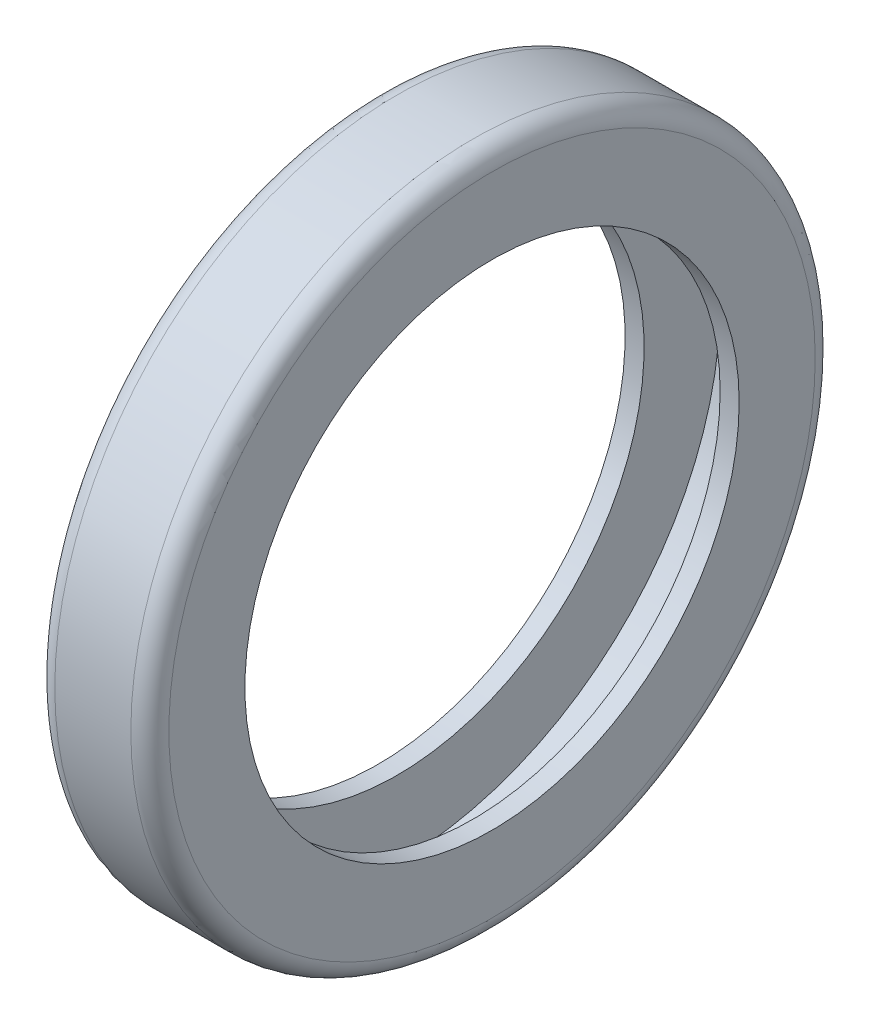
SolidWorks part; units mm, degrees
ref_plane "Plan de face" through (0, 0, 0) normal (0, 0, 1) x (1, 0, 0)
ref_plane "Plan de dessus" through (0, 0, 0) normal (0, 1, 0) x (1, 0, 0)
ref_plane "Plan de droite" through (0, 0, 0) normal (1, 0, 0) x (0, 0, -1)
sketch "Esquisse1" plane through (0, 0, 0) normal (1, 0, 0) x (0, 0, -1)
  line L0 (-23.4478, 0) -> (22.5602, 0) construction
  circle A0 centre (0, 0) radius 21.6
  circle A2 centre (0, 0) radius 20.4
  dimension "D1" = 43.2
  dimension "D2" = 1.2
extrude "Boss.-Extru.3" add sketch "Esquisse1" along normal blind 7.2
sketch "Esquisse4" plane through (7.2, 0, 0) normal (1, 0, 0) x (0, 0, -1)
  circle A0 centre (0, 0) radius 20.4
  circle A1 centre (0, 0) radius 15.6
  dimension "D1" = 31.2
extrude "Boss.-Extru.4" add sketch "Esquisse4" against normal blind 1.2 contours A1 | A0
sketch "Esquisse5" plane through (0, 0, 0) normal (-1, 0, 0) x (0, 0, 1)
  circle A0 centre (0, 0) radius 15.6
  circle A1 centre (0, 0) radius 20.4
extrude "Boss.-Extru.5" add sketch "Esquisse5" against normal blind 1.2
fillet "Congé3" radius 1.2 2 edges at (0, 0, -21.6) (7.2, 0, -21.6)
